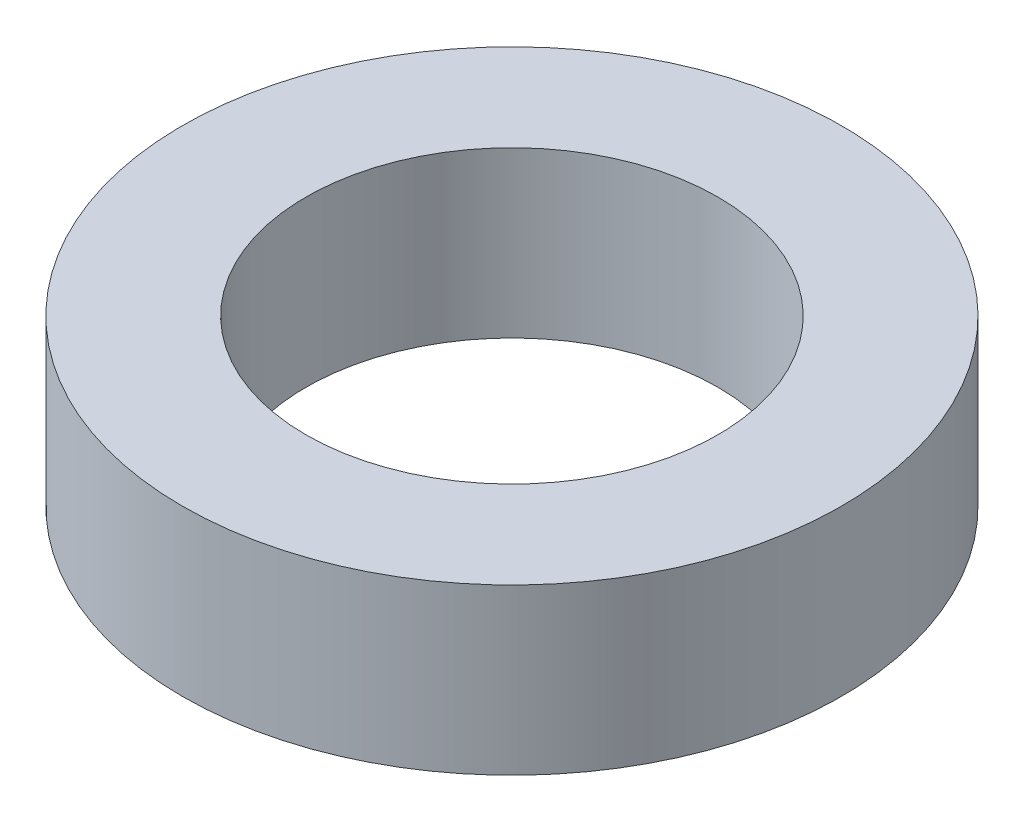
SolidWorks part; units mm, degrees
ref_plane "Front Plane" through (0, 0, 0) normal (0, 0, 1) x (1, 0, 0)
ref_plane "Top Plane" through (0, 0, 0) normal (0, 1, 0) x (1, 0, 0)
ref_plane "Right Plane" through (0, 0, 0) normal (1, 0, 0) x (0, 0, -1)
other "Spacer Diams"
sketch "Sketch1" plane through (0, 0, 0) normal (0, 1, 0) x (1, 0, 0)
  circle A0 centre (0, 0) radius 3.9688
  circle A1 centre (0, 0) radius 6.35
  dimension "Inner Dia" = 7.9375
  dimension "Outer Dia" = 12.7
extrude "Boss-Extrude1" add sketch "Sketch1" along normal blind 3.175
